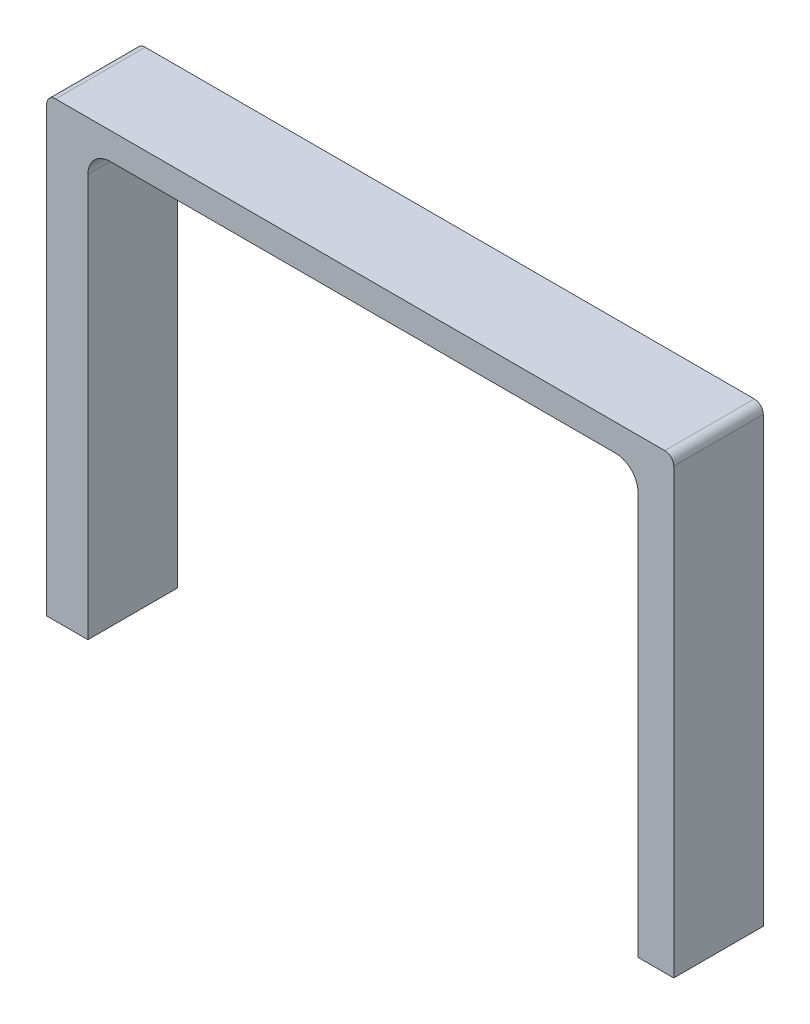
SolidWorks part; units mm, degrees
ref_plane "Front" through (0, 0, 0) normal (0, 0, 1) x (1, 0, 0)
ref_plane "Top" through (0, 0, 0) normal (0, 1, 0) x (1, 0, 0)
ref_plane "Right" through (0, 0, 0) normal (1, 0, 0) x (0, 0, -1)
sketch "Sketch1" plane through (0, 0, 0) normal (0, 0, 1) x (1, 0, 0)
  line L0 (78.7654, -64.135) -> (88.9254, -64.135)
  line L1 (-88.9254, 64.135) -> (88.9254, 64.135)
  line L2 (-88.9254, 64.135) -> (-88.9254, -64.135)
  line L3 (-88.9254, -64.135) -> (-77.2414, -64.135)
  line L4 (88.9254, 64.135) -> (88.9254, -64.135)
  line L5 (-88.9254, 64.135) -> (88.9254, -64.135) construction
  line L6 (-88.9254, -64.135) -> (88.9254, 64.135) construction
  line L7 (78.7654, 56.515) -> (-77.2414, 56.515)
  line L8 (78.7654, 56.515) -> (78.7654, -64.135)
  line L10 (-77.2414, 56.515) -> (-77.2414, -64.135)
  point P0 (0, 0)
  dimension "D1" = 11.684
  dimension "D2" = 156.0068
  dimension "D3" = 7.62
  dimension "D4" = 10.16
  dimension "D5" = 128.27
  dimension "D6" = 177.8508
  dimension "D7" = 128.27
extrude "Boss-Extrude1" add sketch "Sketch1" along normal blind 25.4
fillet "Fillet1" radius 6.35 2 edges at (-77.2414, 56.515, 12.7) (78.7654, 56.515, 12.7)
fillet "Fillet2" radius 2.54 2 edges at (-88.9254, 64.135, 12.7) (88.9254, 64.135, 12.7)
